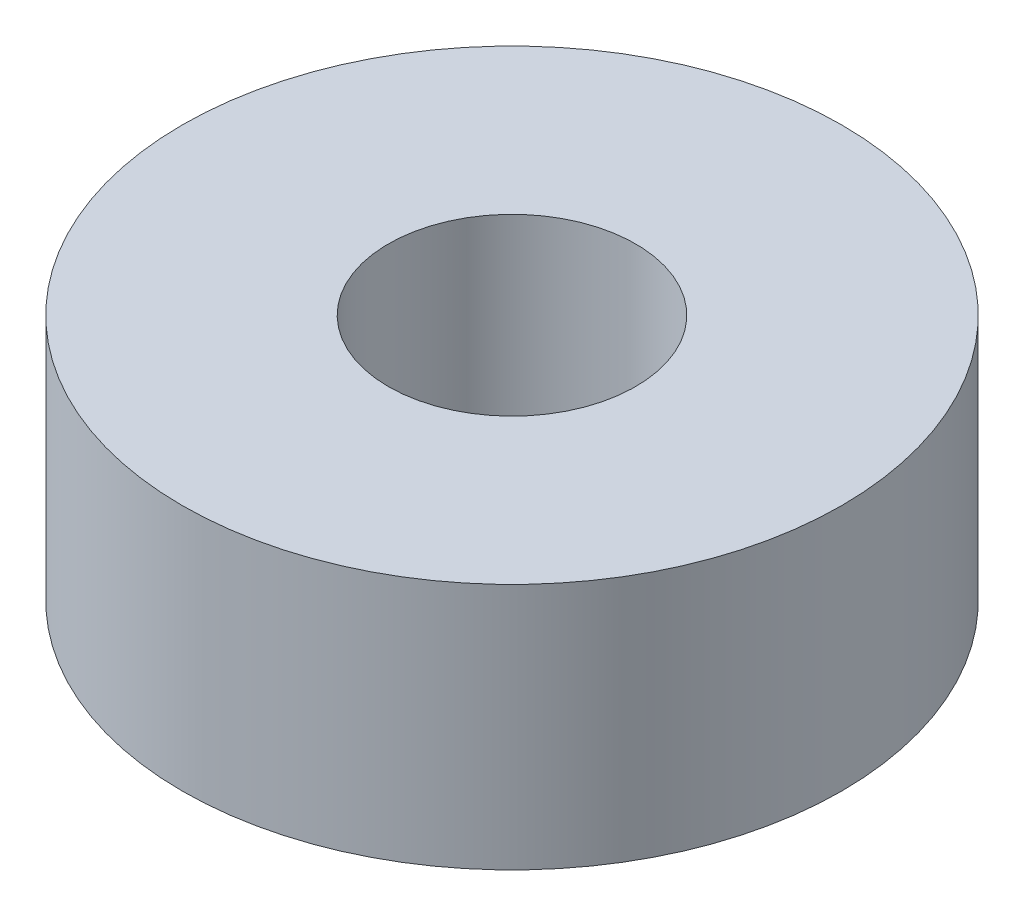
SolidWorks part; units mm, degrees
material "合金钢"
ref_plane "前视基准面" through (0, 0, 0) normal (0, 0, 1) x (1, 0, 0)
ref_plane "上视基准面" through (0, 0, 0) normal (0, 1, 0) x (1, 0, 0)
ref_plane "右视基准面" through (0, 0, 0) normal (1, 0, 0) x (0, 0, -1)
other "Configuration Table"
sketch "草图1" plane through (0, 0, 0) normal (0, 1, 0) x (1, 0, 0)
  circle A0 centre (0, 0) radius 8
  circle A1 centre (0, 0) radius 3
  point P5 (0, 0)
  dimension "D1" = 6
  dimension "D2" = 16
extrude "凸台-拉伸1" add sketch "草图1" along normal blind 6
